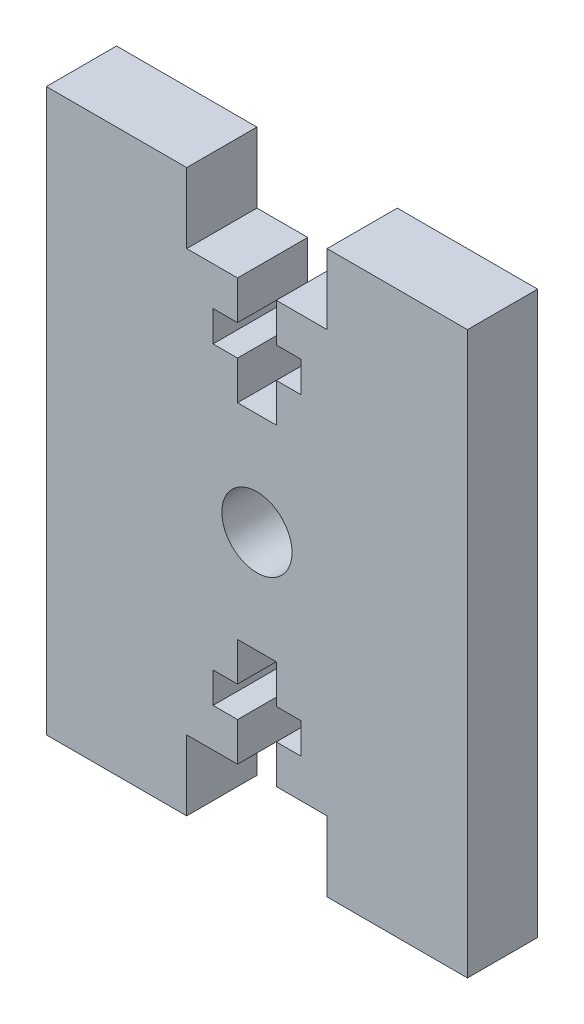
SolidWorks part; units mm, degrees
ref_plane "Front Plane" through (0, 0, 0) normal (0, 0, 1) x (1, 0, 0)
ref_plane "Top Plane" through (0, 0, 0) normal (0, 1, 0) x (1, 0, 0)
ref_plane "Right Plane" through (0, 0, 0) normal (1, 0, 0) x (0, 0, -1)
sketch "Sketch2" plane through (0, 0, 0) normal (0, 0, 1) x (1, 0, 0)
  line L0 (-19.05, 0) -> (-19.05, 25.4)
  line L1 (-19.05, 25.4) -> (-6.35, 25.4)
  line L2 (-6.35, 25.4) -> (-6.35, 19.05)
  line L3 (-6.35, 19.05) -> (-1.7526, 19.05)
  line L4 (-1.7526, 19.05) -> (-1.7526, 15.5496)
  line L5 (-1.7526, 15.5496) -> (-3.9688, 15.5496)
  line L6 (-3.9688, 15.5496) -> (-3.9688, 12.7714)
  line L7 (-3.9688, 12.7714) -> (-1.7526, 12.7714)
  line L8 (-1.7526, 12.7714) -> (-1.7526, 9.271)
  line L9 (-1.7526, 9.271) -> (1.7526, 9.271)
  line L10 (1.7526, 9.271) -> (1.7526, 12.7714)
  line L11 (1.7526, 12.7714) -> (3.9688, 12.7714)
  line L12 (3.9688, 12.7714) -> (3.9688, 15.5496)
  line L13 (3.9688, 15.5496) -> (1.7526, 15.5496)
  line L14 (1.7526, 15.5496) -> (1.7526, 19.05)
  line L15 (1.7526, 19.05) -> (6.35, 19.05)
  line L16 (6.35, 19.05) -> (6.35, 25.4)
  line L17 (6.35, 25.4) -> (19.05, 25.4)
  line L18 (19.05, 25.4) -> (19.05, 0)
  line L19 (-19.05, 0) -> (19.05, 0)
  point P2 (0, 0)
  dimension "D1" = 38.1
  dimension "D2" = 25.4
  dimension "D3" = 6.35
  dimension "D4" = 12.7
  dimension "D5" = 3.5052
  dimension "D6" = 9.779
  dimension "D7" = 2.7781
  dimension "D8" = 7.9375
extrude "Boss-Extrude1" add sketch "Sketch2" along normal blind 6.35
mirror "Mirror1" about plane through (-19.05, 0, 6.35) normal (0, 1, 0) of "Boss-Extrude1"
sketch "Sketch3" plane through (0, 0, 6.35) normal (0, 0, 1) x (1, 0, 0)
  circle A0 centre (0, 0) radius 3.175
  dimension "D1" = 6.35
extrude "Cut-Extrude1" cut sketch "Sketch3" against normal through all
